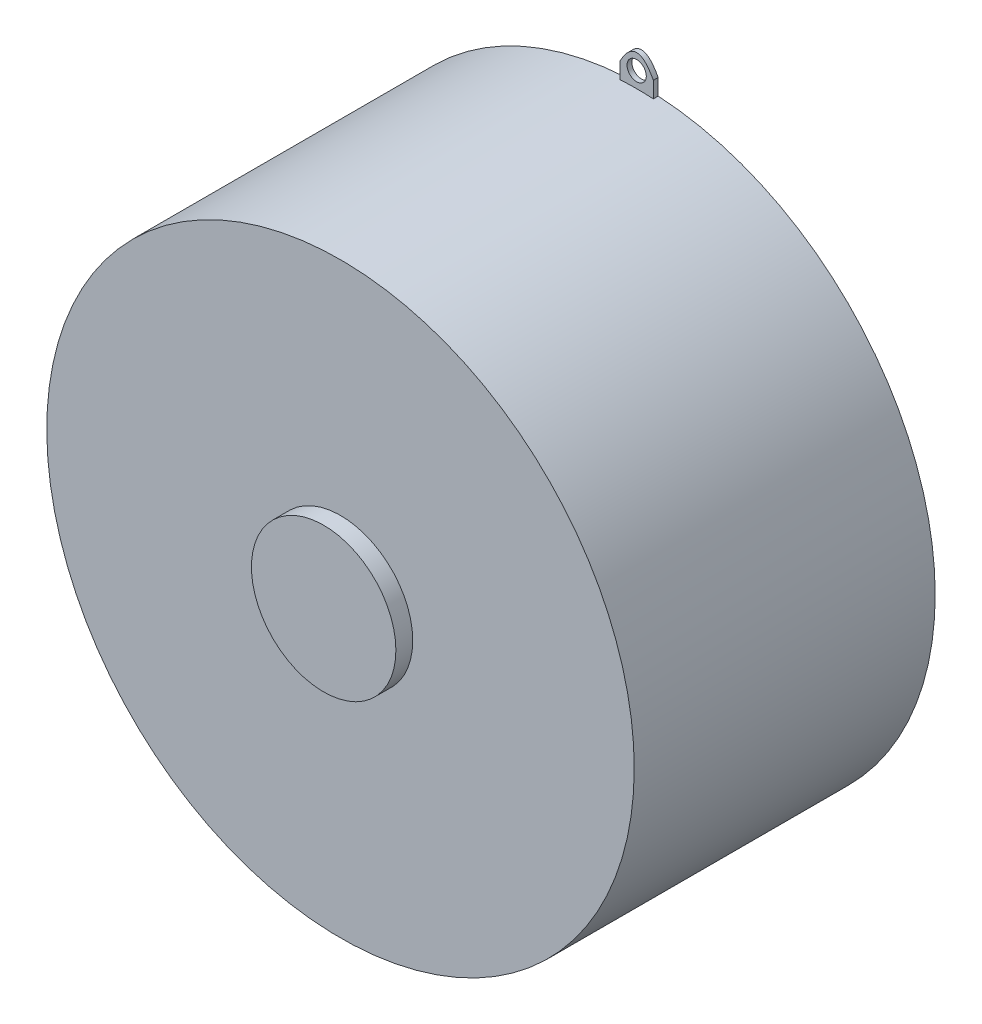
SolidWorks part; units mm, degrees
material "1060 合金"
ref_plane "前视基准面" through (0, 0, 0) normal (0, 0, 1) x (1, 0, 0)
ref_plane "上视基准面" through (0, 0, 0) normal (0, 1, 0) x (1, 0, 0)
ref_plane "右视基准面" through (0, 0, 0) normal (1, 0, 0) x (0, 0, -1)
sketch "草图1" plane through (0, 0, 0) normal (0, 0, 1) x (1, 0, 0)
  circle A0 centre (0, 0) radius 12.2
  dimension "D1" = 24.4
extrude "凸台-拉伸1" add sketch "草图1" along normal blind 12.5
sketch "草图2" plane through (0, 0, 12.5) normal (0, 0, 1) x (1, 0, 0)
  circle A0 centre (0, 0) radius 3
  dimension "D1" = 6
extrude "凸台-拉伸2" add sketch "草图2" along normal blind 0.7
sketch "草图3" plane through (0, 0, 0) normal (0, 0, -1) x (-1, 0, 0)
  circle A0 centre (0, 0) radius 3.25
  dimension "D1" = 6.5
extrude "凸台-拉伸3" add sketch "草图3" along normal blind 1
sketch "草图4" plane through (0, 0, -1) normal (0, 0, -1) x (-1, 0, 0)
  circle A0 centre (0, 0) radius 1
  dimension "D1" = 2
extrude "凸台-拉伸4" add sketch "草图4" along normal blind 4.3
sketch "草图5" plane through (0, 0, 0) normal (0, 0, -1) x (-1, 0, 0)
  circle A0 centre (0, 0) radius 8.25 construction
  circle A1 centre (0, 8.25) radius 0.85
  circle A2 centre (7.1447, 4.125) radius 0.85
  circle A3 centre (7.1447, -4.125) radius 0.85
  circle A4 centre (0, -8.25) radius 0.85
  circle A5 centre (-7.1447, -4.125) radius 0.85
  circle A6 centre (-7.1447, 4.125) radius 0.85
  point P17 (0, 0)
  dimension "D1" = 16.5
  dimension "D2" = 1.7
  dimension "D3" = 6
extrude "切除-拉伸1" cut sketch "草图5" against normal blind 0.35 contours A1 | A6 | A5 | A4 | A3 | A2
sketch "草图6" plane through (0, 0, -1) normal (0, 0, -1) x (-1, 0, 0)
  circle A0 centre (0, 0) radius 1
  circle A1 centre (0, 0) radius 3.25
extrude "切除-拉伸2" cut sketch "草图6" against normal blind 0.5
sketch "草图8" plane through (0, 0, 0) normal (0, 0, -1) x (-1, 0, 0)
  line L0 (0.6945, 12.85) -> (0.6945, 12.1802)
  line L1 (0.6945, 12.1802) -> (0.6945, 12.648)
  line L2 (-0.6945, 12.85) -> (-0.6945, 12.1802)
  line L3 (0, 0) -> (2.1226, 0)
  line L4 (-0.6945, -12.85) -> (-0.6945, -12.1802)
  line L5 (0.6945, -12.1802) -> (0.6945, -12.648)
  line L6 (0.6945, -12.85) -> (0.6945, -12.1802)
  circle A0 centre (0, 12.85) radius 0.4
  circle A1 centre (0, -12.85) radius 0.4
  spline S0 degree 2 poles (0.6945, 12.85) (0, 14.15) (-0.6945, 12.85) knots 0 0 0 1 1 1
  spline S1 degree 2 poles (0.6945, 12.1802) (0, 12.2198) (-0.6945, 12.1802) knots 0 0 0 1 1 1
  spline S2 degree 2 poles (0.6945, -12.1802) (0, -12.2198) (-0.6945, -12.1802) knots 0 0 0 1 1 1
  spline S3 degree 2 poles (0.6945, -12.85) (0, -14.15) (-0.6945, -12.85) knots 0 0 0 1 1 1
  circle M9 centre (0, 0) radius 12.2
extrude "凸台-拉伸6" add sketch "草图8" against normal blind 0.2 contours L0 S0 L2 A0 M9 | S3 L6 L5 L4 A1 M9
extrude "切除-拉伸3" cut sketch "草图9" against normal blind 1.1 and the other way blind 2
sketch "草图9" plane through (-65.6853, 3.3406, 41.6763) normal (0.081, 0.9967, 0) x (0, 0, -1)
  circle A0 centre (43.8722, -65.74) radius 0.4
